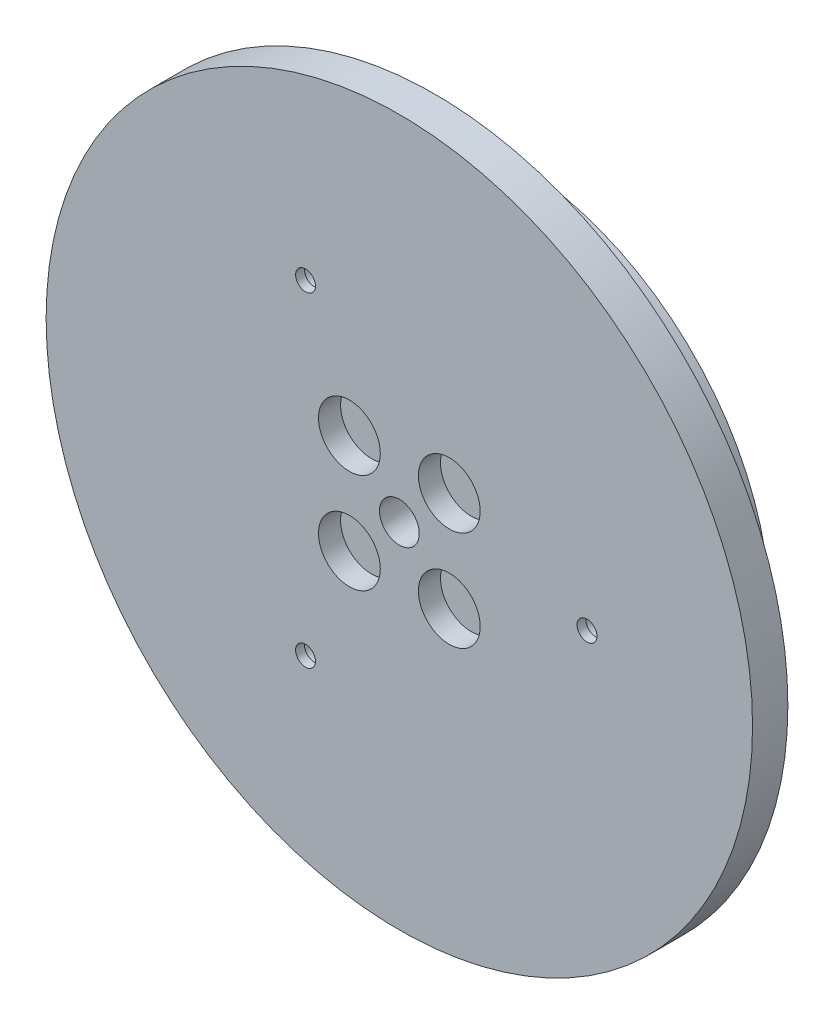
SolidWorks part; units mm, degrees
other "Main Coupler Piece"
other "insert3"
other "insert2"
other "insert1"
other "Back Plate"
ref_plane "Front Plane" through (0, 0, 0) normal (0, 0, 1) x (1, 0, 0)
ref_plane "Top Plane" through (0, 0, 0) normal (0, 1, 0) x (1, 0, 0)
ref_plane "Right Plane" through (0, 0, 0) normal (1, 0, 0) x (0, 0, -1)
sketch "Sketch1" plane through (0, 0, 0) normal (0, 0, 1) x (1, 0, 0)
  circle A0 centre (0, 0) radius 12.5
  circle A1 centre (0, 0) radius 30
  dimension "D1" = 25
  dimension "D2" = 60
extrude "Boss-Extrude1" add sketch "Sketch1" along normal blind 6
sketch "Sketch2" plane through (0, 0, 6) normal (0, 0, 1) x (1, 0, 0)
  line L1 (-5.656, 5.6577) -> (5.656, 5.6577) construction
  line L2 (-5.656, 5.6577) -> (-5.656, -5.6577) construction
  line L3 (-5.656, -5.6577) -> (5.656, -5.6577) construction
  line L4 (5.656, 5.6577) -> (5.656, -5.6577) construction
  circle A0 centre (0, 0) radius 2.25
  circle A1 centre (-5.656, 5.6577) radius 1.5
  circle A2 centre (-5.656, -5.6577) radius 1.5
  circle A3 centre (5.656, -5.6577) radius 1.5
  circle A4 centre (5.656, 5.6577) radius 1.5
  circle A5 centre (0, 0) radius 40
  point P15 (0, -5.6577)
  point P16 (-5.656, 0)
  dimension "D1" = 4.5
  dimension "D4" = 3
  dimension "D5" = 80
  dimension "D2" = 16
  dimension "D3" = 11.3154
extrude "Boss-Extrude2" add sketch "Sketch2" along normal blind 4
sketch "Sketch3" plane through (0, 0, 10) normal (0, 0, 1) x (1, 0, 0)
  circle A0 centre (-5.656, 5.6577) radius 3.5
  circle A1 centre (5.656, 5.6577) radius 3.5
  circle A2 centre (5.656, -5.6577) radius 3.5
  circle A3 centre (-5.656, -5.6577) radius 3.5
  dimension "D1" = 7
extrude "Cut-Extrude1" cut sketch "Sketch3" against normal blind 2.5
sketch "Sketch4" plane through (0, 0, 0) normal (0, 0, -1) x (-1, 0, 0)
  circle A0 centre (-20, 0) radius 5.15
  circle A1 centre (0, -20) radius 5.15
  circle A2 centre (0, 0) radius 20 construction
  circle A3 centre (0, 0) radius 20 construction
  circle A4 centre (20, 0) radius 5.15
  circle A5 centre (0, 0) radius 20 construction
  circle A6 centre (0, 20) radius 5.15
  circle A7 centre (0, 0) radius 20 construction
  circle A8 centre (0, 20) radius 2.65 construction
  circle A9 centre (14.1421, 14.1421) radius 2.65
  circle A10 centre (0, 0) radius 20 construction
  circle A11 centre (20, 0) radius 2.65 construction
  circle A12 centre (0, 0) radius 20 construction
  circle A13 centre (14.1421, -14.1421) radius 2.65
  circle A14 centre (0, 0) radius 20 construction
  circle A15 centre (0, -20) radius 2.65 construction
  circle A16 centre (0, 0) radius 20 construction
  circle A17 centre (-14.1421, -14.1421) radius 2.65
  circle A18 centre (0, 0) radius 20 construction
  circle A19 centre (-20, 0) radius 2.65 construction
  circle A20 centre (0, 0) radius 20 construction
  circle A21 centre (-14.1421, 14.1421) radius 2.65
  circle A22 centre (0, 0) radius 20 construction
  point P17 (0, 0)
  point P39 (0, 0)
  dimension "D1" = 10.3
  dimension "D2" = 40
  dimension "D4" = 5.3
  dimension "D3" = 4
  dimension "D5" = 8
extrude "Cut-Extrude2" cut sketch "Sketch4" against normal blind 3 contours A4
sketch "Sketch5" plane through (0, 0, 7.5) normal (0, 0, 1) x (1, 0, 0)
  circle A0 centre (-5.656, 5.6577) radius 3.5
  circle A1 centre (5.656, 5.6577) radius 3.5
  circle A2 centre (-5.656, -5.6577) radius 3.5
  circle A3 centre (5.656, -5.6577) radius 3.5
extrude "Boss-Extrude3" add sketch "Sketch5" against normal blind 0.2
sketch "Sketch6" plane through (0, 0, 0) normal (0, 0, -1) x (-1, 0, 0)
  circle A0 centre (-21.25, 0) radius 1.125
  circle A1 centre (0, 0) radius 12.5 construction
  circle A2 centre (10.625, 18.403) radius 1.125
  circle A3 centre (10.625, -18.403) radius 1.125
  circle A4 centre (0, 0) radius 30 construction
  point P12 (0, 0)
  dimension "D1" = 21.25
  dimension "D2" = 2.25
  dimension "D3" = 3
extrude "Cut-Extrude3" cut sketch "Sketch6" against normal blind 10
sketch "Sketch7" plane through (0, 0, 0) normal (0, 0, -1) x (-1, 0, 0)
  circle A0 centre (-21.25, 0) radius 3.125
  circle A1 centre (10.625, 18.403) radius 3.125
  circle A2 centre (10.625, -18.403) radius 3.125
  point P9 (10.625, -18.403)
  dimension "D1" = 6.25
extrude "Cut-Extrude4" cut sketch "Sketch7" against normal offset from surface (9 mm away) 1 up to face at (20.125, 0, 10)
sketch "Sketch8" plane through (0, 0, 0) normal (0, 0, -1) x (-1, 0, 0)
  circle A0 centre (20, 0) radius 2
  circle A1 centre (20, 0) radius 5.15 construction
  circle A2 centre (-10, -17.3205) radius 2
  circle A3 centre (-10, 17.3205) radius 2
  circle A4 centre (0, 0) radius 30 construction
  point P11 (0, 0)
  dimension "D1" = 4
  dimension "D2" = 3
extrude "Cut-Extrude5" cut sketch "Sketch8" against normal offset from surface (8 mm away) 2 contours A3 | A2 up to face at (20.125, 0, 10)
sketch "Sketch9" plane through (0, 0, 0) normal (0, 0, -1) x (-1, 0, 0)
  circle A0 centre (-21.25, 0) radius 3
  circle A1 centre (10.625, 18.403) radius 3
  circle A2 centre (10.625, -18.403) radius 3
  dimension "D1" = 6
extrude "Boss-Extrude4" add sketch "Sketch9" along normal blind 0.5 separate body
sketch "Sketch10" plane through (0, 0, -0.5) normal (0, 0, -1) x (-1, 0, 0)
  circle A0 centre (20, 0) radius 5.15
  circle A1 centre (0, 0) radius 12.5
  circle A2 centre (0, 0) radius 30
  circle A3 centre (-10, 17.3205) radius 1.65
  circle A4 centre (-10, -17.3205) radius 1.65
  circle A5 centre (0, 0) radius 12.5 construction
  circle A6 centre (0, 0) radius 30 construction
  circle A7 centre (20, 0) radius 5.15 construction
  dimension "D1" = 3.3
extrude "Boss-Extrude5" add sketch "Sketch10" along normal blind 1.5
sketch "Sketch11" plane through (0, 0, 9) normal (0, 0, -1) x (-1, 0, 0)
  circle A0 centre (-21.25, 0) radius 3
  circle A1 centre (10.625, 18.403) radius 3
  circle A2 centre (10.625, -18.403) radius 3
  circle A4 centre (-21.25, 0) radius 1.5
  circle A5 centre (10.625, 18.403) radius 1.5
  circle A6 centre (10.625, -18.403) radius 1.5
  dimension "D1" = 6
  dimension "D2" = 3
extrude "Boss-Extrude6" add sketch "Sketch11" along normal blind 3 separate body
